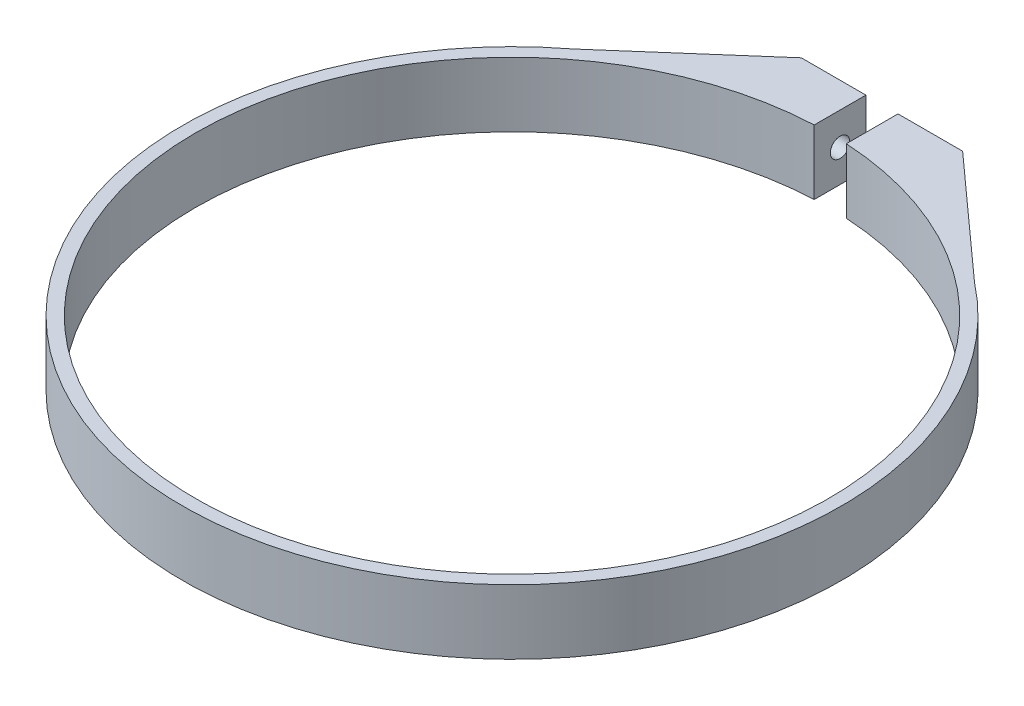
SolidWorks part; units mm, degrees
ref_plane "Front Plane" through (0, 0, 0) normal (0, 0, 1) x (1, 0, 0)
ref_plane "Top Plane" through (0, 0, 0) normal (0, 1, 0) x (1, 0, 0)
ref_plane "Right Plane" through (0, 0, 0) normal (1, 0, 0) x (0, 0, -1)
ref_plane "Plane1" through (0, 10, 0) normal (0, 1, 0) x (1, 0, 0)
sketch "Sketch1" plane through (0, 10, 0) normal (0, 1, 0) x (1, 0, 0)
  line L0 (2.8172, 56.9189) -> (2.8172, 48.9189)
  line L1 (-2.1828, 48.9514) -> (-2.1828, 56.9514)
  line L2 (-2.1828, 56.9514) -> (-12.1828, 56.9514)
  line L3 (-12.1828, 56.9514) -> (-31.0026, 40.4949)
  line L4 (31.3959, 40.1907) -> (12.8172, 56.9189)
  line L5 (12.8172, 56.9189) -> (2.8172, 56.9189)
  arc A0 (2.8172, 48.9189) -> (-2.1828, 48.9514) centre (0, 0) ccw
  arc A1 (-31.0026, 40.4949) -> (31.3959, 40.1907) centre (0, 0) ccw
extrude "Boss-Extrude1" add sketch "Sketch1" against normal blind 10
sketch "Sketch2" plane through (0, 0, 0) normal (0, 0, 1) x (1, 0, 0)
  line L0 (49, 10) -> (0, 10)
  line L1 (0, 10) -> (0, 0)
  line L2 (0, 0) -> (49, 0)
  line L3 (49, 0) -> (49, 10)
  line L4 (0, 10) -> (0, 0) construction
revolve "Cut-Revolve1" cut sketch "Sketch2" angle 360 about L4
hole_wizard "Ø2.5 (2.5) Diameter Hole1" positions "Sketch4" profile "Sketch3" hole size "Ø2.5" standard "ANSI Metric"
sketch "Sketch4" plane through (2.8172, 0, 0) normal (-1, 0, 0) x (0, 0, 1)
  point P0 (-52.9189, 5)
sketch "Sketch3" plane through (2.8172, 5, -52.9189) normal (0, 1, 0) x (0, 0, 1)
  line L0 (0, 0) -> (0, 48.1828)
  line L1 (0, 48.1828) -> (1.25, 48.1828)
  line L2 (1.25, 48.1828) -> (1.25, 0)
  line L5 (1.25, 0) -> (0, 0)
  line L11 (0, -6.35) -> (0, 107.95) construction
  dimension "Thru Hole Dia." = 2.5
  dimension "Thru Hole Depth" = 48.1828
ref_plane "Plane2" through (-19.6163, 0, 0) normal (-1, 0, 0) x (0, 0, 1)
hole_wizard "CBORE for M2.5 Hex Head Machine Screw1" positions "Sketch6" profile "Sketch5" counterbore size "M2.5" standard "ANSI Metric"
sketch "Sketch6" plane through (-19.6163, 0, 0) normal (-1, 0, 0) x (0, 0, 1)
  point P0 (-52.9514, 5)
sketch "Sketch5" plane through (-19.6163, 5, -52.9514) normal (0, 1, 0) x (0, 0, 1)
  line L0 (0, 0) -> (0, 70.6163)
  line L1 (0, 70.6163) -> (1.5, 70.6163)
  line L3 (1.5, 70.6163) -> (1.5, 12.4335)
  line L4 (1.5, 12.4335) -> (2.5, 12.4335)
  line L5 (2.5, 12.4335) -> (2.5, 0)
  line L7 (2.5, 0) -> (0, 0)
  line L11 (0, -6.35) -> (0, 107.95) construction
  dimension "Thru Hole Dia." = 3
  dimension "Thru Hole Depth" = 70.6163
  dimension "C'Bore Dia." = 5
  dimension "C'Bore Depth" = 12.4335
